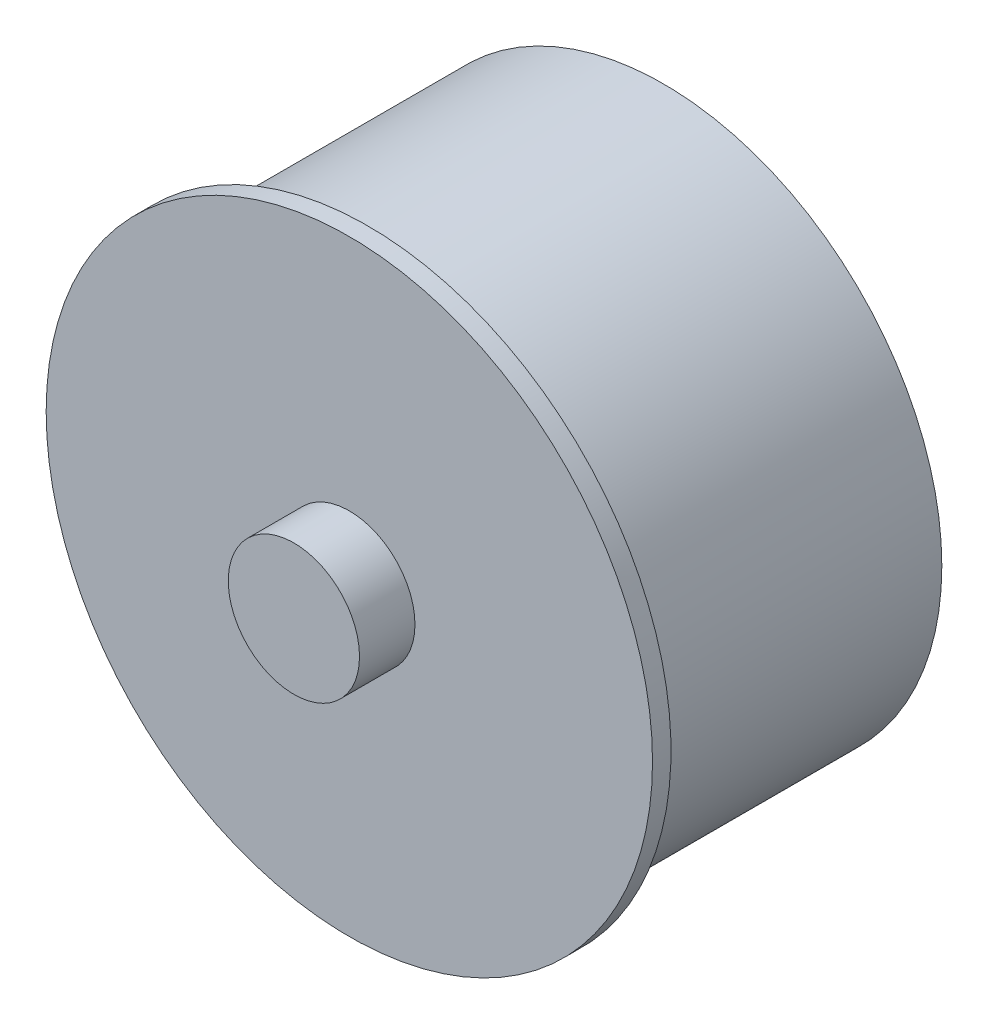
SolidWorks part; units mm, degrees
ref_plane "前视基准面" through (0, 0, 0) normal (0, 0, 1) x (1, 0, 0)
ref_plane "上视基准面" through (0, 0, 0) normal (0, 1, 0) x (1, 0, 0)
ref_plane "右视基准面" through (0, 0, 0) normal (1, 0, 0) x (0, 0, -1)
other "Configuration Table"
sketch "草图1" plane through (0, 0, 0) normal (0, 0, 1) x (1, 0, 0)
  circle A0 centre (0, 0) radius 16.4
  dimension "D1" = 32.8
extrude "凸台-拉伸1" add sketch "草图1" along normal blind 17
sketch "草图2" plane through (0, 0, 17) normal (0, 0, 1) x (1, 0, 0)
  circle A0 centre (0, 0) radius 3.55
  dimension "D1" = 7.1
extrude "凸台-拉伸2" add sketch "草图2" along normal blind 3
sketch "草图3" plane through (0, 0, 0) normal (0, 0, -1) x (-1, 0, 0)
  circle A0 centre (0, 0) radius 10.075
  dimension "D1" = 20.15
extrude "凸台-拉伸3" add sketch "草图3" along normal blind 2 separate body
sketch "草图7" plane through (0, 0, -2) normal (0, 0, -1) x (-1, 0, 0)
  line L0 (0, 0) -> (0, 8) construction
  line L1 (0, 0) -> (8, 0) construction
  line L2 (0, 0) -> (0, -8) construction
  line L3 (0, 0) -> (-8, 0) construction
  circle A0 centre (0, 8) radius 1.05
  circle A1 centre (8, 0) radius 1.05
  circle A2 centre (0, -8) radius 1.05
  circle A3 centre (-8, 0) radius 1.05
  point P13 (0, 0)
  dimension "D1" = 4
extrude "切除-拉伸3" cut sketch "草图7" against normal blind 10 contours A0 | A1 | A2 | A3
sketch "Sketch3" plane through (0, 0, 0) normal (0, 0, -1) x (-1, 0, 0)
  circle A0 centre (0, 0) radius 15.05
  circle A1 centre (0, 0) radius 16.4
extrude "Cut-Extrude3" cut sketch "Sketch3" against normal blind 16
